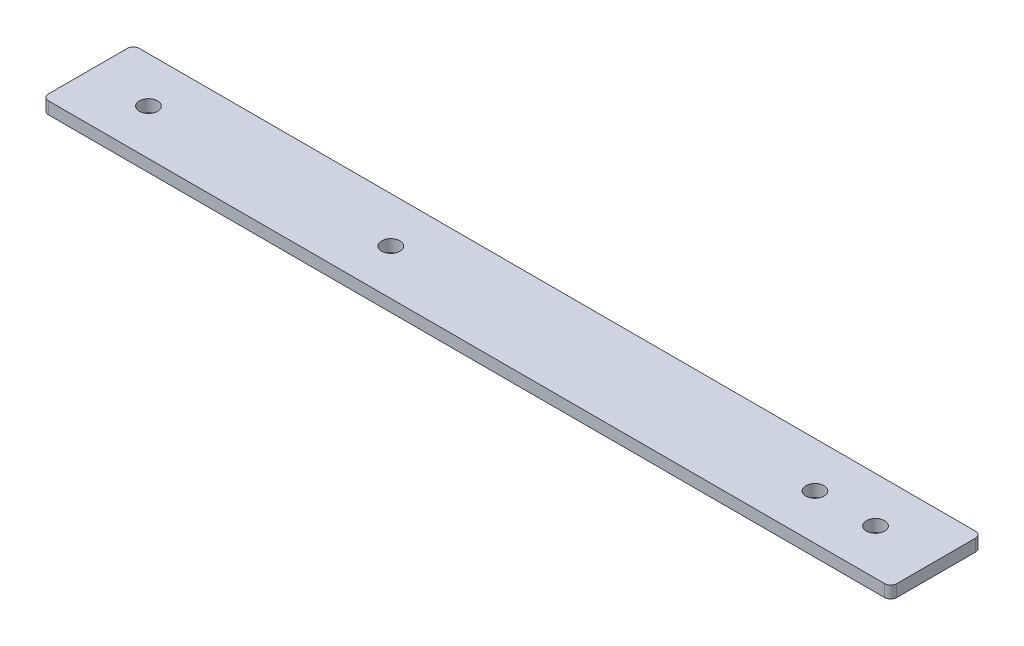
SolidWorks part; units mm, degrees
ref_plane "Front Plane" through (0, 0, 0) normal (0, 0, 1) x (1, 0, 0)
ref_plane "Top Plane" through (0, 0, 0) normal (0, 1, 0) x (1, 0, 0)
ref_plane "Right Plane" through (0, 0, 0) normal (1, 0, 0) x (0, 0, -1)
sketch "Sketch1" plane through (0, 0, 0) normal (0, 1, 0) x (1, 0, 0)
  line L0 (0, 7.5) -> (140, 7.5)
  line L1 (0, 0) -> (140, 0)
  line L2 (0, 0) -> (0, 15)
  line L3 (0, 15) -> (140, 15)
  line L4 (140, 0) -> (140, 15)
  circle A0 centre (10, 7.5) radius 1.5
  circle A1 centre (50, 7.5) radius 1.5
  point P11 (0, 0)
  dimension "D3" = 10
  dimension "D4" = 40
  dimension "D1" = 15
  dimension "D2" = 140
extrude "Boss-Extrude1" add sketch "Sketch1" along normal blind 2 contours A1 L0 L4 L3 L2 A0 | A1 L0 A0 L2 L1 L4
fillet "Fillet1" radius 1 4 edges at (140, 1, 0) (140, 1, -15) (0, 1, 0) (0, 1, -15)
sketch "Sketch2" plane through (0, 2, 0) normal (0, 1, 0) x (1, 0, 0)
  line L0 (140, 1) -> (140, 14) construction
  circle A0 centre (130, 7.5) radius 1.5
  circle A2 centre (120, 7.5) radius 1.5
  dimension "D1" = 10
  dimension "D2" = 3
  dimension "D3" = 3
  dimension "D4" = 10
extrude "Cut-Extrude1" cut sketch "Sketch2" against normal blind 10
